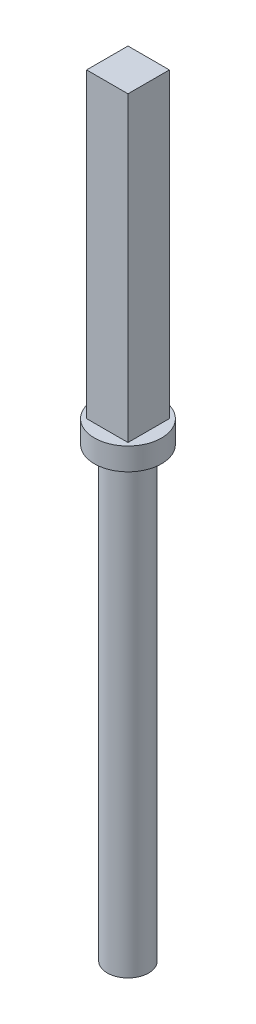
SolidWorks part; units mm, degrees
ref_plane "Front Plane" through (0, 0, 0) normal (0, 0, 1) x (1, 0, 0)
ref_plane "Top Plane" through (0, 0, 0) normal (0, 1, 0) x (1, 0, 0)
ref_plane "Right Plane" through (0, 0, 0) normal (1, 0, 0) x (0, 0, -1)
sketch "Sketch2" plane through (0, 0, 0) normal (0, 1, 0) x (1, 0, 0)
  circle A0 centre (0, 0) radius 1.85
  dimension "D1" = 3.7
extrude "Boss-Extrude1" add sketch "Sketch2" along normal blind 40
sketch "Sketch3" plane through (0, 40, 0) normal (0, 1, 0) x (1, 0, 0)
  circle A0 centre (0, 0) radius 3
  dimension "D1" = 6
extrude "Boss-Extrude2" add sketch "Sketch3" along normal blind 2
sketch "Sketch4" plane through (0, 42, 0) normal (0, 1, 0) x (1, 0, 0)
  line L1 (-1.85, -1.85) -> (1.85, -1.85)
  line L2 (-1.85, -1.85) -> (-1.85, 1.85)
  line L3 (-1.85, 1.85) -> (1.85, 1.85)
  line L4 (1.85, -1.85) -> (1.85, 1.85)
  line L5 (-1.85, -1.85) -> (1.85, 1.85) construction
  line L6 (-1.85, 1.85) -> (1.85, -1.85) construction
  point P0 (0, 0)
  dimension "D1" = 3.7
  dimension "D2" = 3.7
extrude "Boss-Extrude3" add sketch "Sketch4" along normal blind 27
